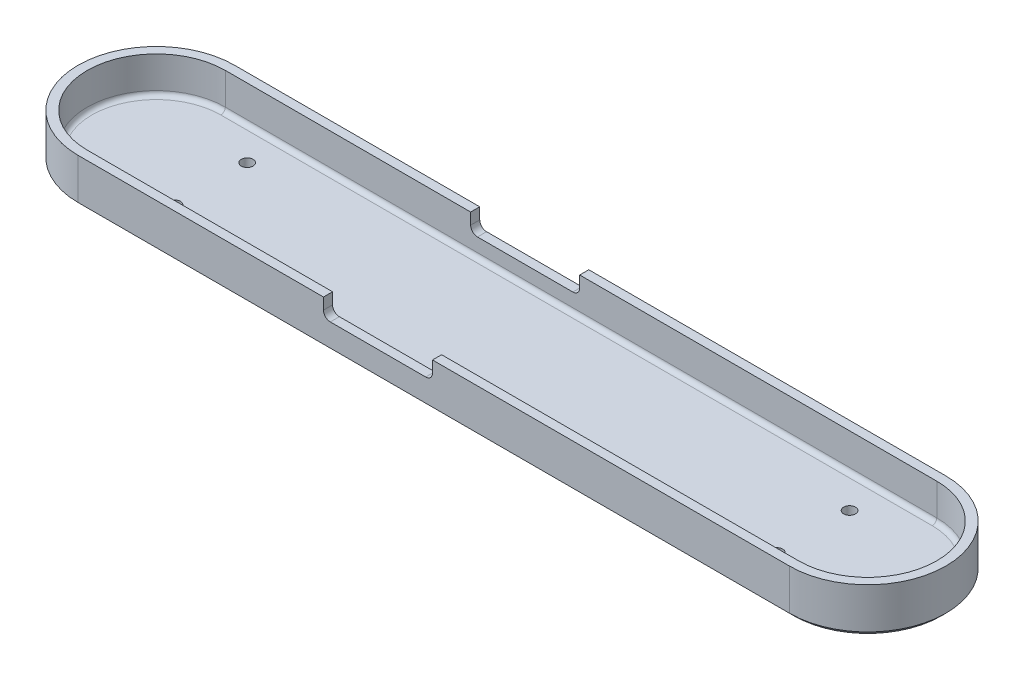
SolidWorks part; units mm, degrees
material "PLA"
ref_plane "Front Plane" through (0, 0, 0) normal (0, 0, 1) x (1, 0, 0)
ref_plane "Top Plane" through (0, 0, 0) normal (0, 1, 0) x (1, 0, 0)
ref_plane "Right Plane" through (0, 0, 0) normal (1, 0, 0) x (0, 0, -1)
sketch "Sketch1" plane through (0, 0, 0) normal (0, 1, 0) x (1, 0, 0)
  line L0 (-99.441, 0) -> (99.441, 0) construction
  line L1 (0, -55.9739) -> (0, 55.9739) construction
  line L2 (-99.441, 19.304) -> (99.441, 19.304)
  line L3 (-99.441, -19.304) -> (99.441, -19.304)
  arc A0 (-99.441, 19.304) -> (-99.441, -19.304) centre (-99.441, 0) ccw
  arc A1 (99.441, 19.304) -> (99.441, -19.304) centre (99.441, 0) cw
  circle A2 centre (-99.441, 0) radius 19.05 construction
  point P4 (0, 0)
  point P10 (0, 0)
  dimension "D2" = 0.254
  dimension "D3" = 38.1
  dimension "D1" = 198.882
extrude "MainBlock" add sketch "Sketch1" along normal blind 2.54
sketch "Sketch2" plane through (0, 0, 0) normal (0, -1, 0) x (1, 0, 0)
  line L0 (0, 0) -> (0, 50000) construction
  line L1 (-99.441, 21.844) -> (99.441, 21.844)
  line L2 (-99.441, -19.304) -> (99.441, -19.304)
  line L3 (99.441, 19.304) -> (-99.441, 19.304)
  line L5 (99.441, 19.304) -> (-99.441, 19.304)
  line L6 (-95.25, 0) -> (49904.75, 0) construction
  line L7 (99.441, -19.304) -> (-99.441, -19.304)
  line L8 (-99.441, -21.844) -> (99.441, -21.844)
  arc A0 (-99.441, 21.844) -> (-99.441, -21.844) centre (-99.441, 0) ccw
  arc A1 (99.441, 19.304) -> (99.441, -19.304) centre (99.441, 0) cw
  arc A2 (-99.441, 19.304) -> (-99.441, -19.304) centre (-99.441, 0) ccw
  arc A3 (99.441, -19.304) -> (99.441, 19.304) centre (99.441, 0) ccw
  arc A4 (-99.441, 19.304) -> (-99.441, -19.304) centre (-99.441, 0) ccw
  arc A6 (99.441, 21.844) -> (99.441, -21.844) centre (99.441, 0) cw
  point P0 (0, 19.304)
  point P15 (0, 21.844)
  point P16 (0, -19.304)
  point P19 (0, -21.844)
  dimension "D2" = 2.54
  dimension "2.1" = 43.688
  dimension "D1" = 0
extrude "Boss-Extrude1" add sketch "Sketch2" against normal blind 12.7
sketch "Sketch3" plane through (0, 0, 0) normal (0, -1, 0) x (1, 0, 0)
  line L0 (0, 0) -> (50000, 0) construction
  line L1 (0, 0) -> (0, 50000) construction
  line L2 (-99.441, 0.9216) -> (-99.441, 50000.9216) construction
  arc A0 (-99.441, 21.844) -> (-99.441, -21.844) centre (-99.441, 0) ccw construction
  arc A1 (-99.441, 21.844) -> (-99.441, -21.844) centre (-99.441, 0) ccw construction
  circle A2 centre (0, 10.16) radius 1.651 construction
  circle A3 centre (-84.201, 10.16) radius 1.651
  circle A4 centre (84.201, 10.16) radius 1.651
  circle A5 centre (84.201, -10.16) radius 1.651
  circle A6 centre (-84.201, -10.16) radius 1.651
  circle A7 centre (0, -10.16) radius 1.651 construction
  dimension "D1" = 3.302
  dimension "D4" = 3.302
  dimension "D2" = 10.16
  dimension "D3" = 10.16
  dimension "D5" = 15.24
extrude "Mount-Holes" cut sketch "Sketch3" against normal through all
fillet "Fillet1" radius 1.27 4 edges at (118.745, 2.54, 0) (0, 2.54, 19.304) (-118.745, 2.54, 0) (0, 2.54, -19.304)
chamfer "Chamfer1" distance 1.27 angle 45 4 edges at (0, 0, 21.844) (-121.285, 0, 0) (121.285, 0, 0) (0, 0, -21.844)
sketch "Sketch4" plane through (0, 12.7, 0) normal (0, 1, 0) x (1, 0, 0)
  line L0 (-30.861, 21.844) -> (-30.861, 19.304)
  line L1 (-99.441, 21.844) -> (99.441, 21.844) construction
  line L2 (-99.441, 19.304) -> (99.441, 19.304) construction
  line L3 (-30.861, 19.304) -> (-0.381, 19.304)
  line L4 (-0.381, 19.304) -> (-0.381, 21.844)
  line L5 (-0.381, 21.844) -> (-30.861, 21.844)
  line L6 (-15.621, 21.844) -> (-15.621, 19.304) construction
  line L7 (-99.441, 0) -> (-99.441, 21.844) construction
  arc A0 (-99.441, 19.304) -> (-99.441, -19.304) centre (-99.441, 0) ccw construction
  arc A1 (-99.441, 19.304) -> (-99.441, -19.304) centre (-99.441, 0) ccw construction
  dimension "D1" = 83.82
  dimension "D2" = 30.48
extrude "Stabilizer-Mount-Cutout" cut sketch "Sketch4" against normal blind 5.08
mirror "Mirror1" about plane through (0, 0, 0) normal (0, 0, 1) of "Stabilizer-Mount-Cutout"
fillet "Fillet2" radius 1.905 4 edges at (-0.381, 7.62, -20.574) (-30.861, 7.62, -20.574) (-30.861, 7.62, 20.574) (-0.381, 7.62, 20.574)
equation "\"D4@Sketch3\"=\"D1@Sketch3\""
